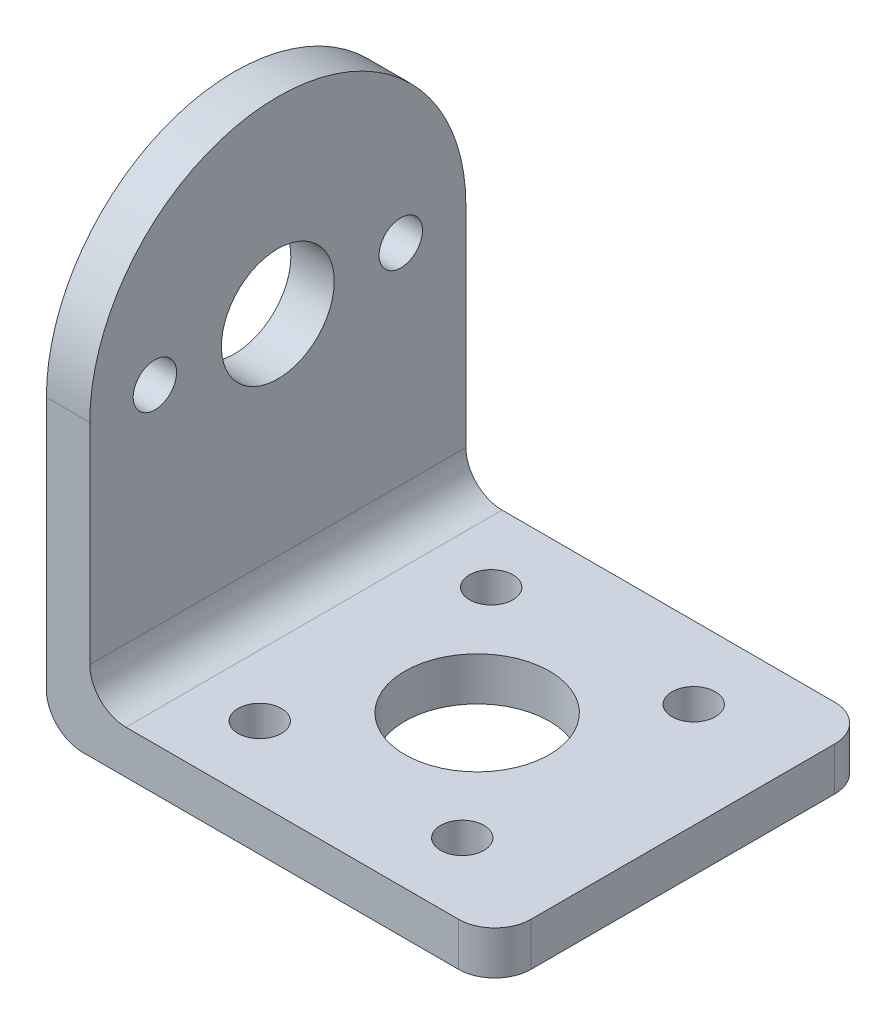
SolidWorks part; units mm, degrees
ref_plane "Front Plane" through (0, 0, 0) normal (0, 0, 1) x (1, 0, 0)
ref_plane "Top Plane" through (0, 0, 0) normal (0, 1, 0) x (1, 0, 0)
ref_plane "Right Plane" through (0, 0, 0) normal (1, 0, 0) x (0, 0, -1)
sketch "Sketch1" plane through (0, 0, 0) normal (0, 0, 1) x (1, 0, 0)
  line L0 (0, 2.5) -> (0, 33)
  line L1 (0, 33) -> (3, 33)
  line L2 (3, 33) -> (3, 5.5)
  line L3 (5.5, 3) -> (31, 3)
  line L4 (31, 3) -> (31, 0)
  line L5 (31, 0) -> (2.5, 0)
  arc A0 (0, 2.5) -> (2.5, 0) centre (2.5, 2.5) ccw
  arc A1 (3, 5.5) -> (5.5, 3) centre (5.5, 5.5) ccw
  point P9 (0, 0)
  dimension "D5" = 2.5
  dimension "D1" = 31
  dimension "D2" = 33
  dimension "D3" = 3
  dimension "D4" = 3
extrude "Boss-Extrude2" add sketch "Sketch1" along normal mid plane 26
fillet "Fillet1" radius 2.5 2 edges at (31, 1.5, -13) (31, 1.5, 13)
sketch "Sketch3" plane through (3, 0, 0) normal (1, 0, 0) x (0, 0, -1)
  line L1 (-13, 5.5) -> (-13, 33) construction
  line L3 (13, 5.5) -> (13, 33) construction
  line L6 (-13, 20) -> (-13, 33)
  line L7 (-13, 33) -> (13, 33)
  line L8 (13, 33) -> (13, 20)
  arc A0 (-13, 20) -> (13, 20) centre (0, 20) cw
  line M5 (13, 5.5) -> (13, 33)
  line M6 (13, 33) -> (-13, 33)
  line M7 (-13, 33) -> (-13, 5.5)
extrude "Cut-Extrude1" cut sketch "Sketch3" against normal mid plane 26 contours A0 L7 M7 | A0 M6 M5
sketch "Sketch4" plane through (3, 0, 0) normal (1, 0, 0) x (0, 0, -1)
  circle A0 centre (-8.5, 20) radius 1.5
  circle A1 centre (8.5, 20) radius 1.5
  circle A2 centre (0, 20) radius 3.9
  dimension "D1" = 3
  dimension "D4" = 7.8
  dimension "D2" = 17
  dimension "D3" = 4.5
extrude "Cut-Extrude2" cut sketch "Sketch4" against normal mid plane 26
sketch "Sketch5" plane through (0, 0, 0) normal (0, -1, 0) x (1, 0, 0)
  line L0 (2.5, 13) -> (28.5, 13) construction
  line L1 (2.5, 13) -> (2.5, -13) construction
  circle A0 centre (23.75, 8) radius 1.5
  circle A1 centre (23.75, -8) radius 1.5
  circle A2 centre (9.75, 8) radius 1.5
  circle A3 centre (9.75, -8) radius 1.5
  circle A4 centre (16.7805, 0) radius 5
  dimension "D1" = 3
  dimension "D2" = 16
  dimension "D3" = 16
  dimension "D4" = 14
  dimension "D5" = 14
  dimension "D7" = 7.25
  dimension "D8" = 10
  dimension "D6" = 5
extrude "Cut-Extrude3" cut sketch "Sketch5" against normal mid plane 26
